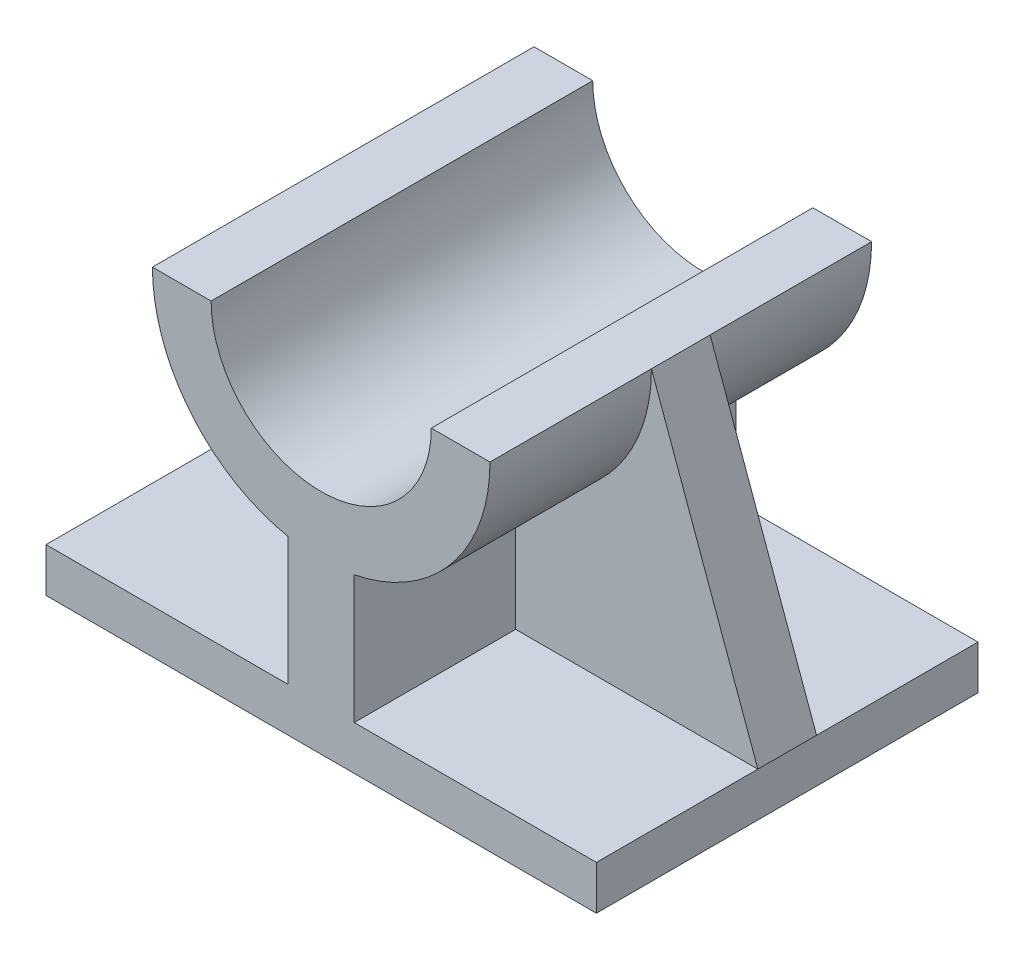
SolidWorks part; units mm, degrees
ref_plane "Front Plane" through (0, 0, 0) normal (0, 0, 1) x (1, 0, 0)
ref_plane "Top Plane" through (0, 0, 0) normal (0, 1, 0) x (1, 0, 0)
ref_plane "Right Plane" through (0, 0, 0) normal (1, 0, 0) x (0, 0, -1)
sketch "Sketch1" plane through (0, 0, 0) normal (0, 0, 1) x (1, 0, 0)
  line L0 (-37.5, 43) -> (30.8586, 43) construction
  line L1 (-37.5, 3) -> (37.5, 3)
  line L2 (-37.5, 3) -> (-37.5, -3)
  line L3 (-37.5, -3) -> (37.5, -3)
  line L4 (37.5, 3) -> (37.5, -3)
  line L5 (-37.5, 3) -> (37.5, -3) construction
  line L6 (-37.5, -3) -> (37.5, 3) construction
  line L7 (-4.5, 3) -> (4.5, 3)
  line L8 (-4.5, 3) -> (0, 3)
  line L9 (4.5, 3) -> (4.5, 20.4445)
  line L10 (-4.5, 3) -> (-4.5, 20.4445)
  line L11 (-23, 43) -> (-15, 43)
  line L12 (15, 43) -> (23, 43)
  arc A0 (-15, 43) -> (15, 43) centre (0, 43) ccw
  arc A1 (-23, 43) -> (-4.5, 20.4445) centre (0, 43) ccw
  arc A2 (4.5, 20.4445) -> (23, 43) centre (0, 43) ccw
  point P0 (0, 0)
  dimension "D3" = 46
  dimension "D4" = 30
  dimension "D1" = 75
  dimension "D2" = 6
  dimension "D5" = 40
  dimension "D6" = 9
  dimension "D7" = 4.5
extrude "Boss-Extrude1" add sketch "Sketch1" against normal blind 52 contours L9 A2 L12 A0 L11 A1 L10 L1 L7 | L4 L1 L7 L2 L3
sketch "Sketch7" plane through (0, 0, 0) normal (0, 0, 1) x (1, 0, 0)
  line L0 (37.5, 3) -> (4.5, 3)
  line L1 (4.5, 3) -> (4.5, 20.4445)
  line L2 (23, 43) -> (37.5, 3)
  arc A0 (23, 43) -> (4.5, 20.4445) centre (0, 43) cw
  arc A1 (4.5, 20.4445) -> (23, 43) centre (0, 43) ccw construction
  line M1 (4.5, 3) -> (4.5, 20.4445)
  arc M2 (4.5, 20.4445) -> (23, 43) centre (0, 43) ccw
  line M12 (37.5, 3) -> (4.5, 3)
extrude "Boss-Extrude2" add sketch "Sketch7" against normal blind 8 from offset 22 contours L2 M2 M1 M12
